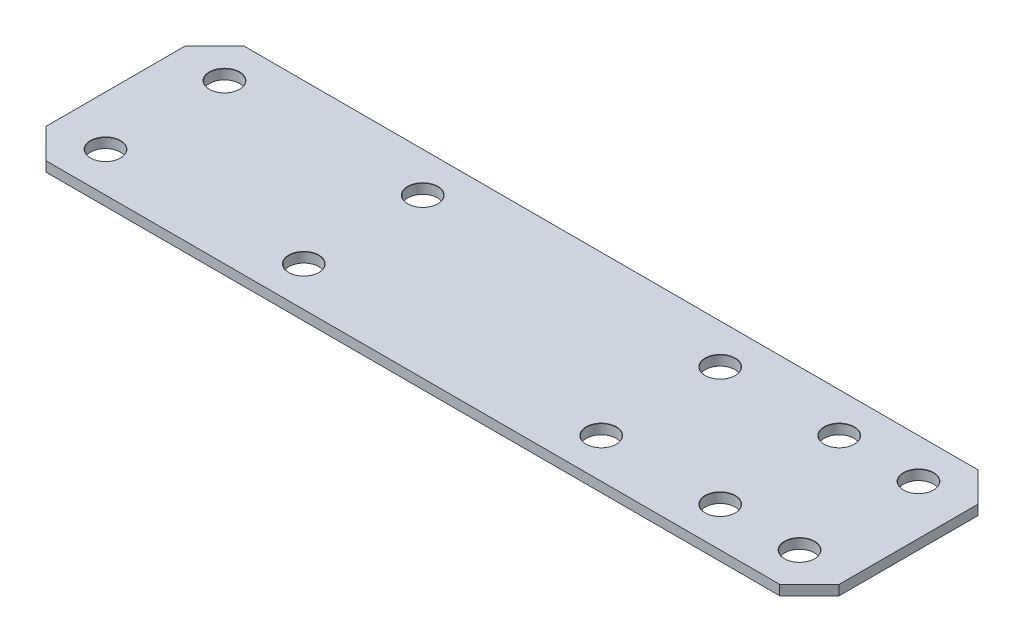
SolidWorks part; units mm, degrees
ref_plane "前视基准面" through (0, 0, 0) normal (0, 0, 1) x (1, 0, 0)
ref_plane "上视基准面" through (0, 0, 0) normal (0, 1, 0) x (1, 0, 0)
ref_plane "右视基准面" through (0, 0, 0) normal (1, 0, 0) x (0, 0, -1)
other "Configuration Table"
sketch "草图1" plane through (0, 0, 0) normal (0, 1, 0) x (1, 0, 0)
  line L1 (0, 0) -> (80, 0)
  line L2 (0, 0) -> (0, 20)
  line L3 (0, 20) -> (80, 20)
  line L4 (80, 0) -> (80, 20)
  dimension "D1" = 20
  dimension "D2" = 80
extrude "凸台-拉伸1" add sketch "草图1" along normal blind 1 contours L3 L4 L1 L2
sketch "草图2" plane through (0, 1, 0) normal (0, 1, 0) x (1, 0, 0)
  line L0 (0, 0) -> (0, 20) construction
  line L1 (5, 16) -> (75, 16)
  line L2 (5, 16) -> (5, 4)
  line L3 (5, 4) -> (75, 4)
  line L4 (75, 16) -> (75, 4)
  line L5 (80, 0) -> (80, 20) construction
  line L6 (0, 20) -> (80, 20) construction
  point P10 (25, 16)
  point P11 (55, 16)
  point P12 (25, 4)
  point P13 (55, 4)
  dimension "D1" = 5
  dimension "D2" = 5
  dimension "D3" = 12
  dimension "D4" = 4
  dimension "D5" = 20
  dimension "D6" = 20
  dimension "D7" = 20
  dimension "D8" = 20
hole_wizard "Ø3.0mm 暗销孔1" positions "3D草图1" profile "草图3" hole size "Ø3.0" standard "GB" end condition through all
sketch3d "3D草图1"
  line L0 (0, 1, -20) -> (80, 1, -20) construction
  line L1 (80, 1, 0) -> (80, 1, -20) construction
  line L2 (5, 1, -16) -> (75, 1, -16) construction
  line L3 (5, 1, -4) -> (75, 1, -4) construction
  point P0 (5, 1, -16)
  point P3 (5, 1, -4)
  point P13 (25, 1, -16)
  point P16 (55, 1, -16)
  point P19 (25, 1, -4)
  point P22 (55, 1, -4)
  point P29 (75, 1, -4)
  point P31 (75, 1, -16)
  point P41 (67, 1, -16)
  point P45 (67, 1, -4)
  dimension "D1" = 12
  dimension "D2" = 5
  dimension "D5" = 8
  dimension "D3" = 4
  dimension "D4" = 5
  dimension "D6" = 8
sketch "草图3" plane through (5, 1, -16) normal (1, 0, 0) x (0, 0, 1)
  line L0 (0, 0) -> (0, 1)
  line L1 (0, 1) -> (1.5, 1)
  line L2 (1.5, 1) -> (1.5, 0.025)
  line L3 (1.5, 0.025) -> (1.525, 0)
  line L5 (1.525, 0) -> (0, 0)
  line L6 (-1.5, 0.025) -> (-1.525, 0) construction
  line L11 (0, -6.35) -> (0, 107.95) construction
  dimension "通孔孔直径" = 3
  dimension "通孔孔深度" = 1
  dimension "近端锥形沉头孔直径" = 3.05
  dimension "近端锥形沉头孔角度" = 90
chamfer "倒角1" distance 3 angle 45 4 edges at (0, 0.5, 0) (0, 0.5, -20) (80, 0.5, 0) (80, 0.5, -20)
